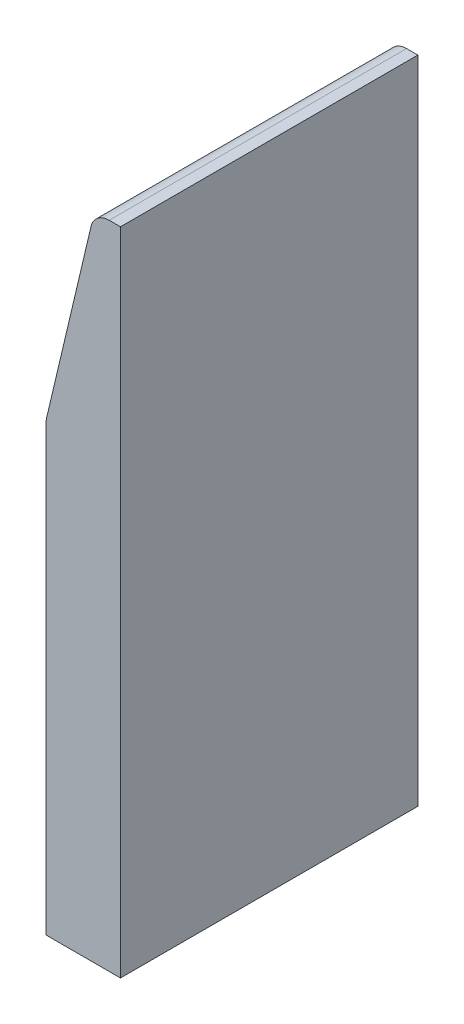
SolidWorks part; units mm, degrees
material "Q355"
ref_plane "前视基准面" through (0, 0, 0) normal (0, 0, 1) x (1, 0, 0)
ref_plane "上视基准面" through (0, 0, 0) normal (0, 1, 0) x (1, 0, 0)
ref_plane "右视基准面" through (0, 0, 0) normal (1, 0, 0) x (0, 0, -1)
sketch "草图1" plane through (0, 0, 0) normal (0, 0, 1) x (1, 0, 0)
  line L0 (0, 0) -> (0, 125)
  line L1 (0, 125) -> (13, 180)
  line L2 (13, 180) -> (20, 180)
  line L3 (20, 180) -> (20, 0)
  line L4 (20, 0) -> (0, 0)
  dimension "D1" = 7
  dimension "D2" = 180
  dimension "D3" = 125
  dimension "D4" = 20
extrude "凸台-拉伸1" add sketch "草图1" along normal mid plane 80
chamfer "倒角1" distance 5 angle 45 4 edges at (0, 0, 0) (10, 0, 40) (20, 0, 0) (10, 0, -40)
fillet "圆角1" radius 5 2 edges at (13, 180, 0) (0, 125, 0)
